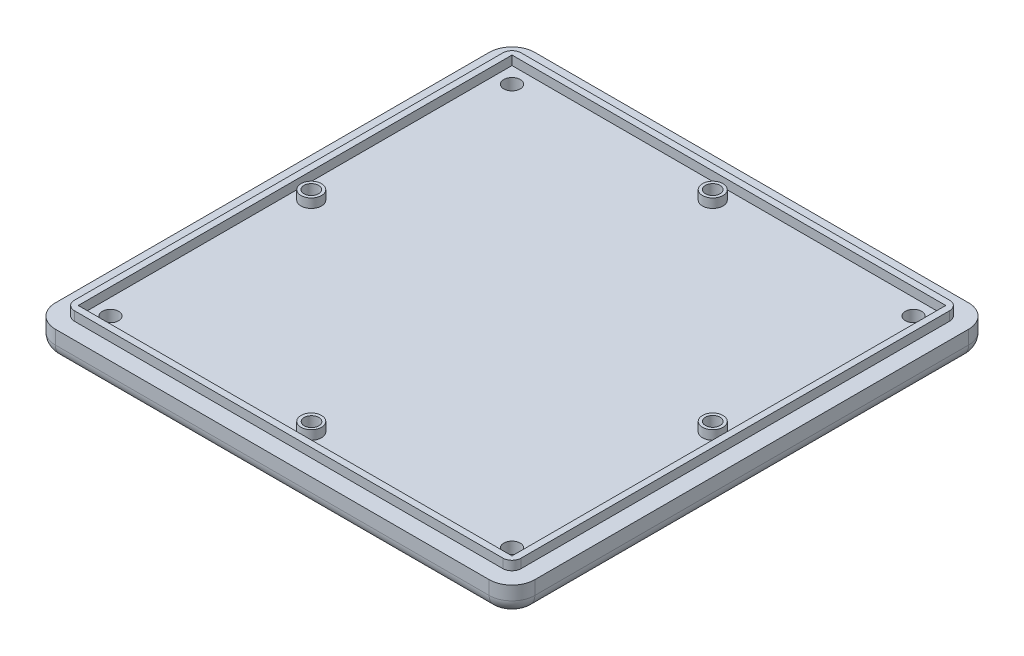
SolidWorks part; units mm, degrees
ref_plane "Front Plane" through (0, 0, 0) normal (0, 0, 1) x (1, 0, 0)
ref_plane "Top Plane" through (0, 0, 0) normal (0, 1, 0) x (1, 0, 0)
ref_plane "Right Plane" through (0, 0, 0) normal (1, 0, 0) x (0, 0, -1)
sketch "Sketch1" plane through (0, 0, 0) normal (0, 1, 0) x (1, 0, 0)
  line L0 (0, 105) -> (105, 0) construction
  line L1 (5, 0) -> (100, 0)
  line L2 (0, 5) -> (0, 100)
  line L3 (5, 105) -> (100, 105)
  line L4 (105, 5) -> (105, 100)
  line L5 (0, 0) -> (105, 105) construction
  arc A0 (100, 0) -> (105, 5) centre (100, 5) ccw
  arc A1 (0, 100) -> (5, 105) centre (5, 100) cw
  arc A2 (100, 105) -> (105, 100) centre (100, 100) cw
  arc A3 (5, 0) -> (0, 5) centre (5, 5) cw
  dimension "D3" = 5
  dimension "D1" = 105
  dimension "D2" = 105
extrude "Boss-Extrude1" add sketch "Sketch1" along normal blind 6
fillet "Fillet1" radius 3 8 edges at (1.4645, 0, -103.5355) (52.5, 0, -105) (103.5355, 0, -103.5355) (105, 0, -52.5) (103.5355, 0, -1.4645) (1.4645, 0, -1.4645) (0, 0, -52.5) (52.5, 0, 0)
sketch "Sketch2" plane through (0, 0, 0) normal (0, -1, 0) x (1, 0, 0)
  line L0 (100, -5) -> (96.4645, -8.5355) construction
  line L1 (100, -100) -> (96.4645, -96.4645) construction
  line L2 (5, -5) -> (8.5355, -8.5355) construction
  line L3 (5, -100) -> (8.5355, -96.4645) construction
  point P12 (0, 0)
  dimension "D1" = 5
  dimension "D2" = 5
  dimension "D3" = 5
  dimension "D4" = 5
hole_wizard "CSK for M3 Flat Head Machine Screw1" positions "3DSketch1" profile "Sketch4" countersink size "M3" standard "ANSI Metric" end condition through all
sketch3d "3DSketch1"
  point P0 (8.5355, 0, -8.5355)
  point P3 (8.5355, 0, -96.4645)
  point P6 (96.4645, 0, -96.4645)
  point P9 (96.4645, 0, -8.5355)
sketch "Sketch4" plane through (8.5355, 0, -8.5355) normal (1, 0, 0) x (0, 0, -1)
  line L0 (0, 0) -> (0, 6)
  line L1 (0, 6) -> (1.8, 6)
  line L2 (1.8, 6) -> (1.8, 1.35)
  line L3 (1.8, 1.35) -> (3.15, 0)
  line L5 (3.15, 0) -> (0, 0)
  line L6 (-1.8, 1.35) -> (-3.15, 0) construction
  line L11 (0, -6.35) -> (0, 107.95) construction
  dimension "Thru Hole Dia." = 3.6
  dimension "Thru Hole Depth" = 6
  dimension "Near C'Sink Dia." = 6.3
  dimension "Near C'Sink Angle" = 90
sketch "Sketch5" plane through (0, 6, 0) normal (0, 1, 0) x (1, 0, 0)
  line L0 (100, 100) -> (101.4142, 101.4142) construction
  line L1 (7, 5) -> (98, 5)
  line L2 (5, 7) -> (5, 98)
  line L3 (7, 100) -> (98, 100)
  line L4 (100, 7) -> (100, 98)
  line L5 (100, 100) -> (5, 100)
  line L6 (100, 100) -> (100, 5)
  line L7 (100, 5) -> (5, 5)
  line L8 (5, 100) -> (5, 5)
  line L9 (5, 100) -> (3.5858, 101.4142) construction
  line L10 (5, 5) -> (3.5858, 3.5858)
  line L11 (100, 5) -> (101.4142, 3.5858) construction
  line L13 (5.5858, 3.5858) -> (99.4142, 3.5858)
  line L14 (3.5858, 5.5858) -> (3.5858, 99.4142)
  line L15 (5.5858, 101.4142) -> (99.4142, 101.4142)
  line L16 (101.4142, 5.5858) -> (101.4142, 99.4142)
  arc A0 (98, 5) -> (100, 7) centre (98, 7) ccw
  arc A1 (7, 5) -> (5, 7) centre (7, 7) cw
  arc A2 (5, 98) -> (7, 100) centre (7, 98) cw
  arc A3 (98, 100) -> (100, 98) centre (98, 98) cw
  arc A4 (101.4142, 5.5858) -> (99.4142, 3.5858) centre (99.4142, 5.5858) cw
  arc A5 (3.5858, 5.5858) -> (5.5858, 3.5858) centre (5.5858, 5.5858) ccw
  arc A6 (5.5858, 101.4142) -> (3.5858, 99.4142) centre (5.5858, 99.4142) ccw
  arc A7 (101.4142, 99.4142) -> (99.4142, 101.4142) centre (99.4142, 99.4142) ccw
  point P11 (5, 5)
  point P16 (100, 100)
  dimension "D1" = 2
  dimension "D6" = 2
  dimension "D2" = 2
  dimension "D3" = 2
  dimension "D4" = 2
  dimension "D5" = 2
extrude "Boss-Extrude2" add sketch "Sketch5" along normal blind 2
sketch "Sketch6" plane through (0, 6, 0) normal (0, 1, 0) x (1, 0, 0)
  line L0 (96.4645, 8.5355) -> (96.4645, 96.4645) construction
  line L1 (8.5355, 8.5355) -> (96.4645, 8.5355) construction
  line L2 (8.5355, 8.5355) -> (8.5355, 96.4645) construction
  line L3 (8.5355, 96.4645) -> (96.4645, 96.4645) construction
  circle A0 centre (8.5355, 52.5) radius 2.25
  circle A1 centre (52.5, 8.5355) radius 2.25
  circle A2 centre (96.4645, 52.5) radius 2.25
  circle A3 centre (52.5, 96.4645) radius 2.25
  dimension "D1" = 4.5
  dimension "D2" = 4.5
  dimension "D3" = 4.5
  dimension "D4" = 4.5
extrude "Boss-Extrude3" add sketch "Sketch6" along normal blind 2
hole_wizard "M3 Clearance Hole1" positions "3DSketch2" profile "Sketch8" hole size "M3" standard "ANSI Metric"
sketch3d "3DSketch2"
  line L0 (8.5355, 8, -52.5) -> (8.5355, 6, -52.5) construction
  line L1 (96.4645, 8, -52.5) -> (96.4645, 6, -52.5) construction
  line L2 (52.5, 8, -96.4645) -> (52.5, 6, -96.4645) construction
  point P0 (8.5355, 8, -52.5)
  point P4 (52.5797, 8, -8.5164)
  point P6 (96.4645, 8, -52.5)
  point P10 (52.5, 8, -96.4645)
sketch "Sketch8" plane through (8.5355, 8, -52.5) normal (1, 0, 0) x (0, 0, 1)
  line L0 (0, 0) -> (0, 5.9614)
  line L1 (0, 5.9614) -> (1.6, 5)
  line L2 (1.6, 5) -> (1.6, 0)
  line L5 (1.6, 0) -> (0, 0)
  line L10 (0, 5.9614) -> (-1.6, 5) construction
  line L11 (0, -6.35) -> (0, 107.95) construction
  dimension "Hole Dia." = 3.2
  dimension "Hole Depth" = 5
  dimension "Drill Angle" = 118
